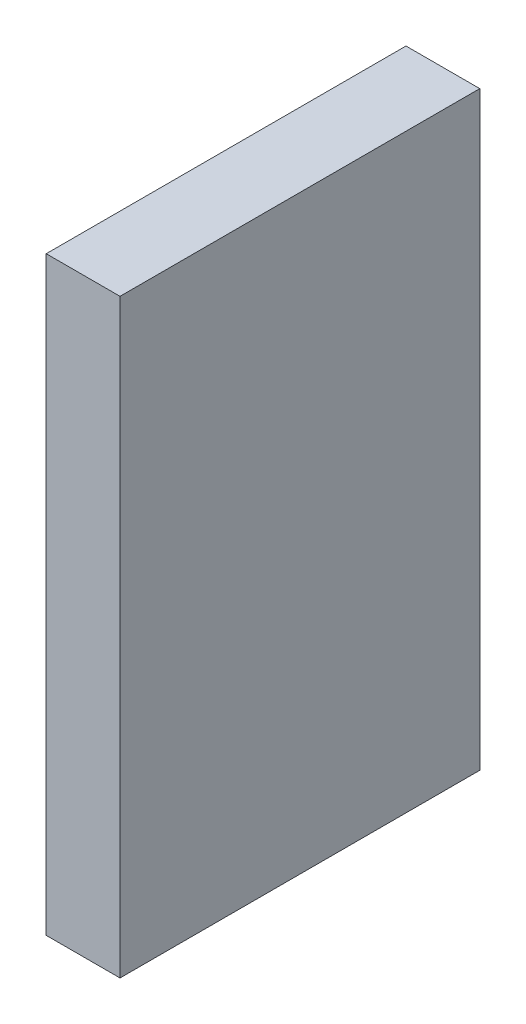
SolidWorks part; units mm, degrees
ref_plane "Front Plane" through (0, 0, 0) normal (0, 0, 1) x (1, 0, 0)
ref_plane "Top Plane" through (0, 0, 0) normal (0, 1, 0) x (1, 0, 0)
ref_plane "Right Plane" through (0, 0, 0) normal (1, 0, 0) x (0, 0, -1)
sketch "Sketch1" plane through (0, 0, 0) normal (0, 0, 1) x (1, 0, 0)
  line L1 (-2, 16) -> (2, 16)
  line L2 (-2, 16) -> (-2, -16)
  line L3 (-2, -16) -> (2, -16)
  line L4 (2, 16) -> (2, -16)
  point P4 (2, 0)
  point P6 (0, 16)
  dimension "D1" = 32
  dimension "D2" = 4
extrude "Boss-Extrude1" add sketch "Sketch1" along normal blind 19.5
